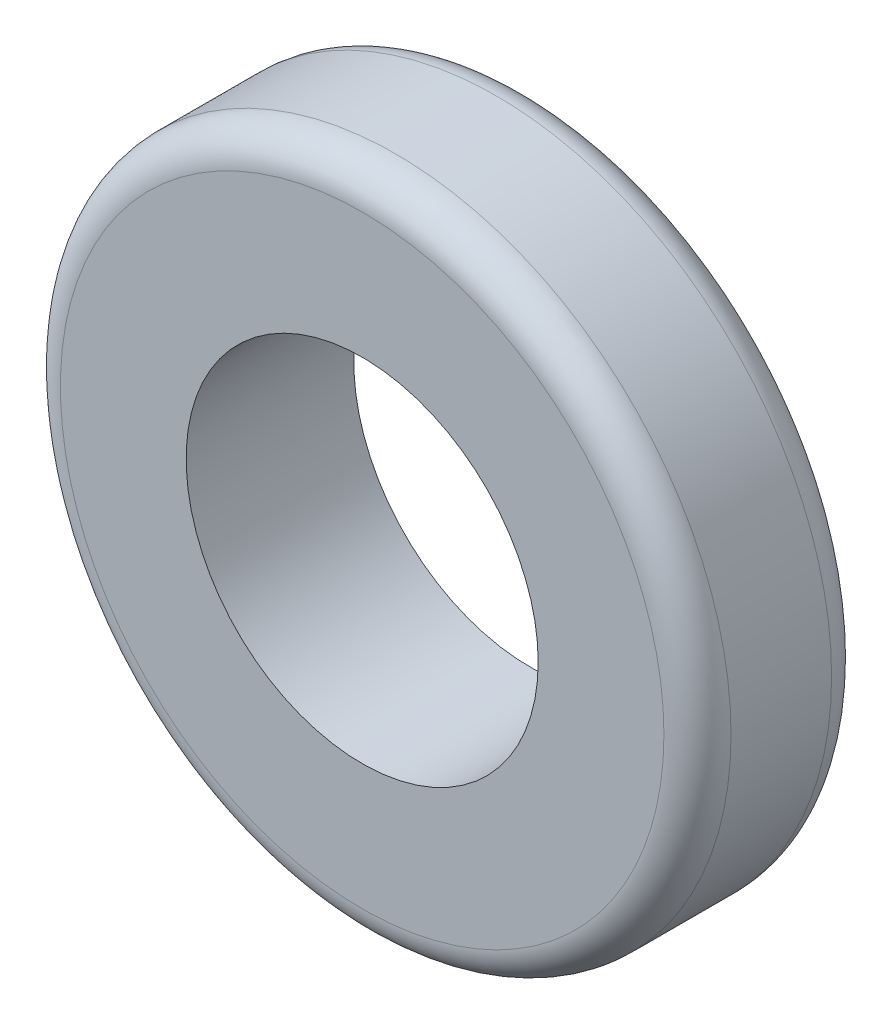
SolidWorks part; units mm, degrees
material "PVC 0.007 Plasticized"
ref_plane "Front Plane" through (0, 0, 0) normal (0, 0, 1) x (1, 0, 0)
ref_plane "Top Plane" through (0, 0, 0) normal (0, 1, 0) x (1, 0, 0)
ref_plane "Right Plane" through (0, 0, 0) normal (1, 0, 0) x (0, 0, -1)
sketch "Sketch1" plane through (0, 0, 0) normal (0, 0, 1) x (1, 0, 0)
  circle A0 centre (0, 0) radius 25.4
  circle A1 centre (0, 0) radius 13.335
  dimension "D1" = 50.8
  dimension "D2" = 26.67
extrude "Boss-Extrude1" add sketch "Sketch1" along normal mid plane 12.7
fillet "Fillet2" radius 2.54 2 edges at (25.4, 0, -6.35) (25.4, 0, 6.35)
